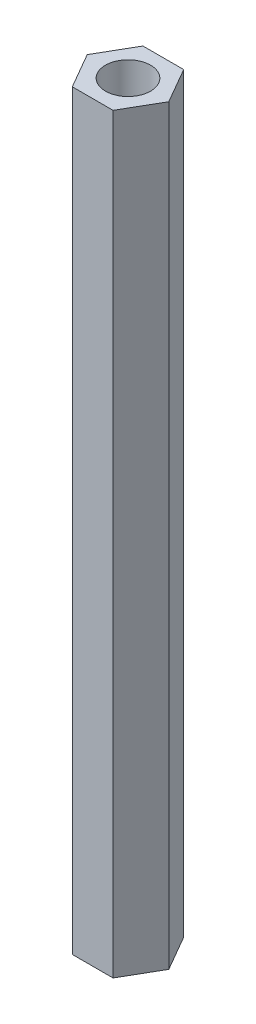
SolidWorks part; units mm, degrees
ref_plane "前视基准面" through (0, 0, 0) normal (0, 0, 1) x (1, 0, 0)
ref_plane "上视基准面" through (0, 0, 0) normal (0, 1, 0) x (1, 0, 0)
ref_plane "右视基准面" through (0, 0, 0) normal (1, 0, 0) x (0, 0, -1)
sketch "草图1" plane through (0, 0, 0) normal (0, 1, 0) x (1, 0, 0)
  line L1 (2.7135, 0) -> (1.3568, 2.35)
  line L2 (1.3568, 2.35) -> (-1.3568, 2.35)
  line L3 (-1.3568, 2.35) -> (-2.7135, 0)
  line L4 (-2.7135, 0) -> (-1.3568, -2.35)
  line L5 (-1.3568, -2.35) -> (1.3568, -2.35)
  line L6 (1.3568, -2.35) -> (2.7135, 0)
  circle A0 centre (0, 0) radius 2.35 construction
  circle A1 centre (0, 0) radius 1.5
extrude "凸台-拉伸1" add sketch "草图1" along normal blind 50
